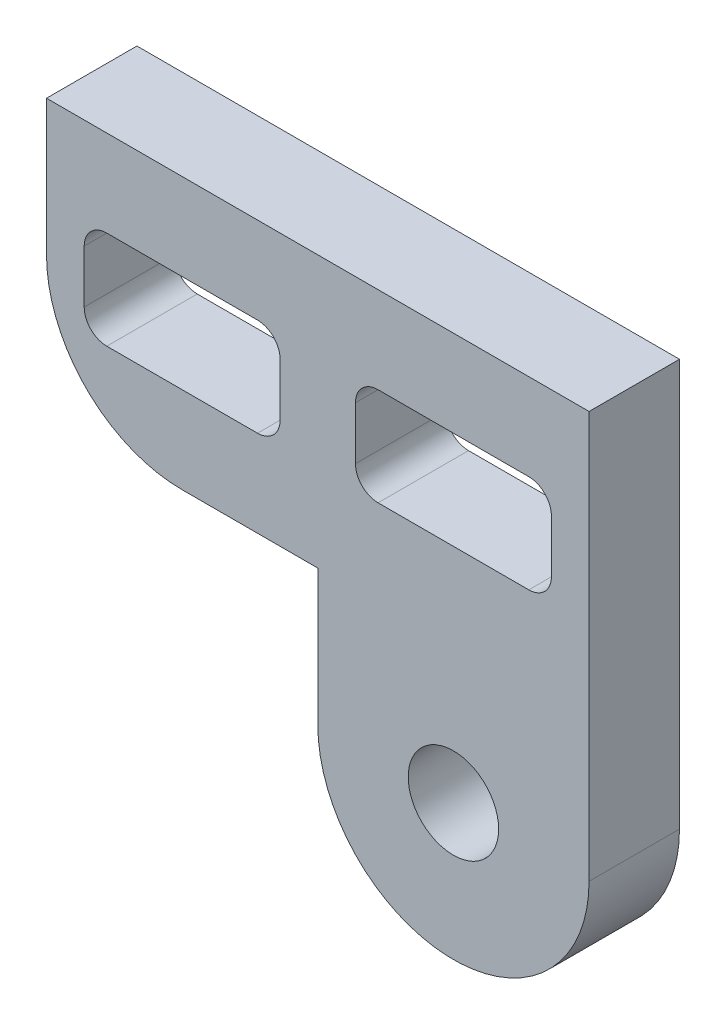
SolidWorks part; units mm, degrees
ref_plane "Alzado" through (0, 0, 0) normal (0, 0, 1) x (1, 0, 0)
ref_plane "Planta" through (0, 0, 0) normal (0, 1, 0) x (1, 0, 0)
ref_plane "Vista lateral" through (0, 0, 0) normal (1, 0, 0) x (0, 0, -1)
sketch "Model" plane through (0, 0, 0) normal (0, 0, 1) x (1, 0, 0)
  line L0 (149.3421, 211.824) -> (158.3421, 211.824)
  line L1 (153.8421, 202.824) -> (149.3421, 202.824)
  line L2 (162.8421, 198.324) -> (162.8421, 211.824)
  line L3 (153.8421, 198.324) -> (153.8421, 202.824)
  line L4 (151.8421, 205.699) -> (146.8421, 205.699)
  line L5 (146.0921, 206.449) -> (146.0921, 208.199)
  line L6 (146.8421, 208.949) -> (151.8421, 208.949)
  line L7 (152.5921, 208.199) -> (152.5921, 206.449)
  line L8 (160.8421, 205.699) -> (155.8421, 205.699)
  line L9 (155.0921, 206.449) -> (155.0921, 208.199)
  line L10 (155.8421, 208.949) -> (160.8421, 208.949)
  line L11 (161.5921, 208.199) -> (161.5921, 206.449)
  line L12 (149.3421, 211.824) -> (144.8421, 211.824)
  line L13 (158.3421, 211.824) -> (162.8421, 211.824)
  line L14 (144.8421, 207.324) -> (144.8421, 211.824)
  arc A0 (144.8421, 207.324) -> (149.3421, 202.824) centre (149.3421, 207.324) ccw
  arc A1 (146.0921, 206.449) -> (146.8421, 205.699) centre (146.8421, 206.449) ccw
  arc A2 (146.8421, 208.949) -> (146.0921, 208.199) centre (146.8421, 208.199) ccw
  arc A3 (152.5921, 208.199) -> (151.8421, 208.949) centre (151.8421, 208.199) ccw
  arc A4 (151.8421, 205.699) -> (152.5921, 206.449) centre (151.8421, 206.449) ccw
  arc A5 (155.0921, 206.449) -> (155.8421, 205.699) centre (155.8421, 206.449) ccw
  arc A6 (155.8421, 208.949) -> (155.0921, 208.199) centre (155.8421, 208.199) ccw
  arc A7 (161.5921, 208.199) -> (160.8421, 208.949) centre (160.8421, 208.199) ccw
  arc A8 (160.8421, 205.699) -> (161.5921, 206.449) centre (160.8421, 206.449) ccw
  circle A9 centre (158.3421, 198.324) radius 1.5
  arc A10 (153.8421, 198.324) -> (162.8421, 198.324) centre (158.3421, 198.324) ccw
extrude "Saliente-Extruir1" add sketch "Model" along normal blind 3
